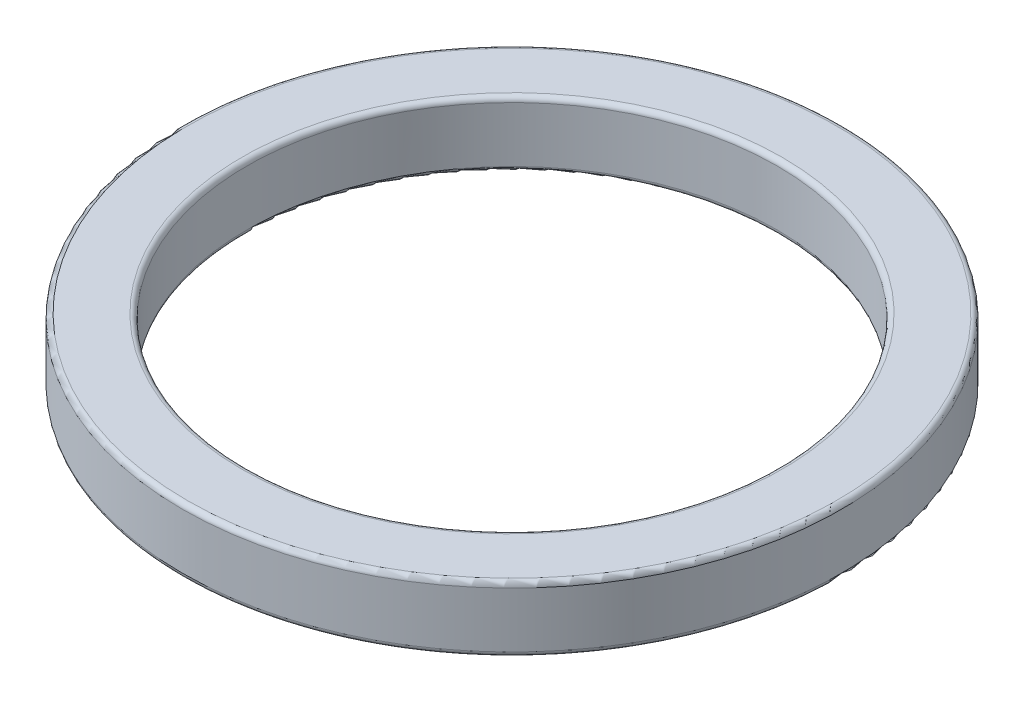
SolidWorks part; units mm, degrees
ref_plane "Plan de face" through (0, 0, 0) normal (0, 0, 1) x (1, 0, 0)
ref_plane "Plan de dessus" through (0, 0, 0) normal (0, 1, 0) x (1, 0, 0)
ref_plane "Plan de droite" through (0, 0, 0) normal (1, 0, 0) x (0, 0, -1)
sketch "Esquisse1" plane through (0, 0, 0) normal (0, 0, 1) x (1, 0, 0)
  line L0 (0, 0) -> (0, 4.3378) construction
  line L2 (5.27, 2.9717) -> (6.55, 2.9717)
  line L3 (5.27, 2.9717) -> (5.27, 1.6717)
  line L4 (5.27, 1.6717) -> (6.55, 1.6717)
  line L5 (6.55, 2.9717) -> (6.55, 1.6717)
  dimension "D1" = 13.1
  dimension "D2" = 10.54
  dimension "D3" = 1.3
revolve "Révolution1" add sketch "Esquisse1" angle 360 about L0
fillet "Congé1" radius 0.1 4 edges at (0, 1.6717, -5.27) (0, 1.6717, -6.55) (0, 2.9717, -6.55) (0, 2.9717, -5.27)
